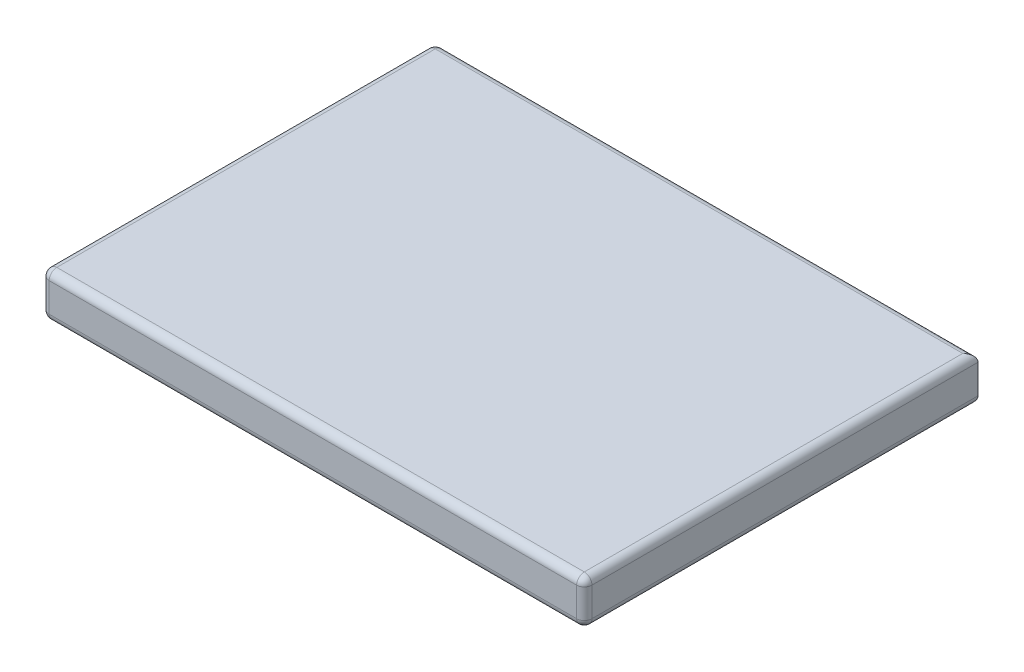
SolidWorks part; units mm, degrees
material "ABS"
ref_plane "Front Plane" through (0, 0, 0) normal (0, 0, 1) x (1, 0, 0)
ref_plane "Top Plane" through (0, 0, 0) normal (0, 1, 0) x (1, 0, 0)
ref_plane "Right Plane" through (0, 0, 0) normal (1, 0, 0) x (0, 0, -1)
sketch "Sketch1" plane through (0, 0, 0) normal (0, 1, 0) x (1, 0, 0)
  line L1 (0, 0) -> (71, 0)
  line L2 (0, 0) -> (0, 51.5)
  line L3 (0, 51.5) -> (71, 51.5)
  line L4 (71, 0) -> (71, 51.5)
  dimension "D1" = 71
  dimension "D2" = 51.5
extrude "Boss-Extrude1" add sketch "Sketch1" along normal blind 5.8
fillet "Fillet1" radius 1 11 edges at (0, 2.9, -51.5) (0, 5.8, -25.75) (0, 0, -25.75) (0, 2.9, 0) (35.5, 5.8, 0) (71, 2.9, 0) (35.5, 0, 0) (71, 0, -25.75) (35.5, 0, -51.5) (71, 5.8, -25.75) (35.5, 5.8, -51.5)
